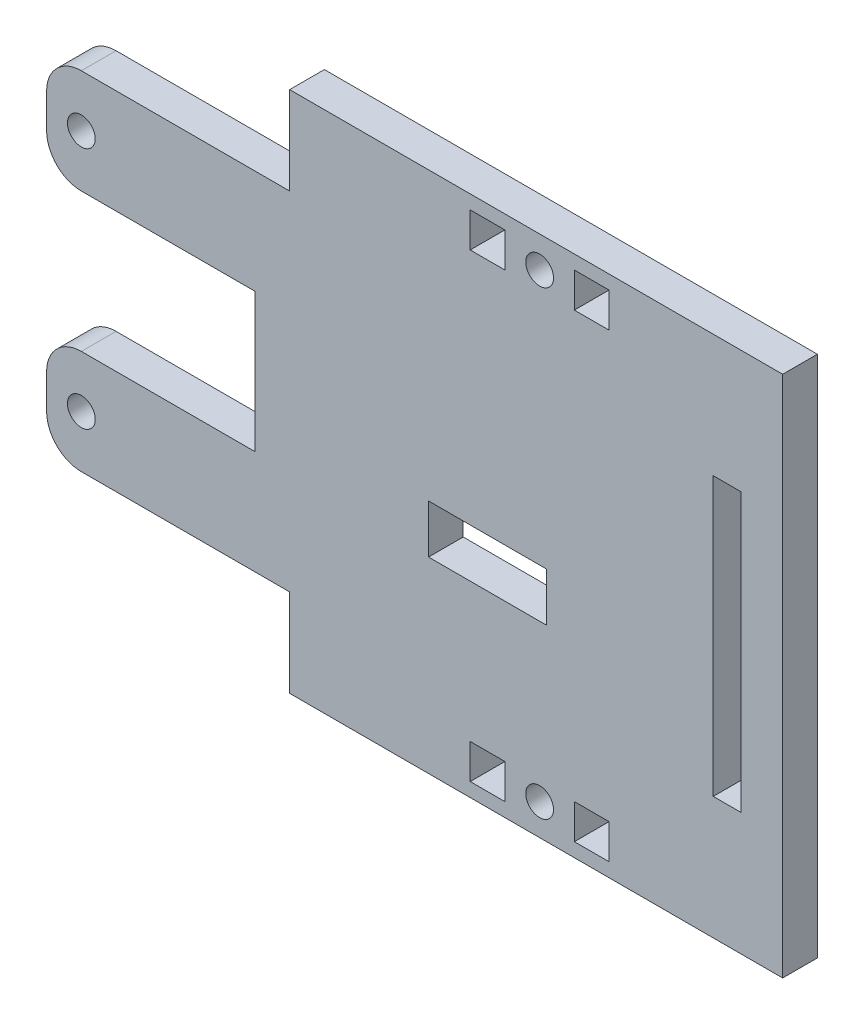
SolidWorks part; units mm, degrees
ref_plane "Plan de face" through (0, 0, 0) normal (0, 0, 1) x (1, 0, 0)
ref_plane "Plan de dessus" through (0, 0, 0) normal (0, 1, 0) x (1, 0, 0)
ref_plane "Plan de droite" through (0, 0, 0) normal (1, 0, 0) x (0, 0, -1)
sketch "Esquisse1" plane through (0, 0, 0) normal (0, 0, 1) x (1, 0, 0)
  line L0 (0, 0) -> (71, 0) construction
  line L1 (0, 37.65) -> (71, 37.65)
  line L2 (71, 37.65) -> (71, -37.65)
  line L3 (0, 37.65) -> (0, -37.65) construction
  line L4 (0, -37.65) -> (71, -37.65)
  line L5 (0, -37.65) -> (0, -25)
  line L6 (0, -25) -> (-35, -25)
  line L7 (-35, -25) -> (-35, -10)
  line L8 (-35, -10) -> (-5, -10)
  line L9 (-5, -10) -> (-5, 10)
  line L10 (-5, 10) -> (-35, 10)
  line L11 (-35, 10) -> (-35, 25)
  line L12 (-35, 25) -> (0, 25)
  line L13 (0, 25) -> (0, 37.65)
  line L14 (-35, 17.5) -> (0, 17.5) construction
  line L16 (37, -3.65) -> (20, -3.65)
  line L17 (37, -3.65) -> (37, -10.65)
  line L18 (37, -10.65) -> (20, -10.65)
  line L19 (20, -3.65) -> (20, -10.65)
  line L20 (37, -3.65) -> (20, -10.65) construction
  line L21 (37, -10.65) -> (20, -3.65) construction
  line L22 (65, 20) -> (61, 20)
  line L23 (65, 20) -> (65, -20)
  line L24 (65, -20) -> (61, -20)
  line L25 (61, 20) -> (61, -20)
  line L26 (65, 20) -> (61, -20) construction
  line L27 (65, -20) -> (61, 20) construction
  circle A0 centre (-30, 17.5) radius 2
  circle A1 centre (-30, -17.5) radius 2
  point P25 (28.5, -7.15)
  point P30 (63, 0)
  point P31 (0, 0)
  line B0 (31, 33.15) -> (41, 33.15) construction
  line B1 (31, 35.65) -> (26, 35.65)
  line B2 (31, 35.65) -> (31, 30.65)
  line B3 (31, 30.65) -> (26, 30.65)
  line B4 (26, 35.65) -> (26, 30.65)
  line B5 (41, 35.65) -> (46, 35.65)
  line B6 (41, 35.65) -> (41, 30.65)
  line B7 (41, 30.65) -> (46, 30.65)
  line B8 (46, 35.65) -> (46, 30.65)
  line B9 (36, 33.15) -> (36, 40.1224) construction
  circle B10 centre (36, 33.15) radius 2
  line B11 (31, -35.65) -> (26, -35.65)
  line B12 (31, -35.65) -> (31, -30.65)
  line B13 (31, -30.65) -> (26, -30.65)
  line B14 (26, -35.65) -> (26, -30.65)
  line B15 (41, -35.65) -> (46, -35.65)
  line B16 (41, -35.65) -> (41, -30.65)
  line B17 (41, -30.65) -> (46, -30.65)
  line B18 (46, -35.65) -> (46, -30.65)
  line B19 (36, -33.15) -> (36, -40.1224) construction
  circle B20 centre (36, -33.15) radius 2
  dimension "D8" = 4
  dimension "D12" = 34
  dimension "D1" = 36
  dimension "D2" = 20
  dimension "D3" = 2
  dimension "D4" = 71
  dimension "D5" = 33.15
  dimension "D6" = 20
  dimension "D7" = 15
  dimension "D9" = 25
  dimension "D10" = 30
  dimension "D11" = 5
  dimension "D13" = 51
  dimension "D14" = 20
  dimension "D15" = 27
  dimension "D16" = 4
  dimension "D17" = 6
  dimension "D18" = 40
  dimension "D19" = 40
sketch_block_instance "Trou M4 plots 5mm-1"
sketch_block "Trou M4 plots 5mm" parameters "D2"=4, "D1"=5, "D3"=5, "D4"=10
sketch_block_instance "Trou M4 plots 5mm-5"
extrude "Boss.-Extru.1" add sketch "Esquisse1" along normal blind 5
fillet "Congé1" radius 5 4 edges at (-35, -25, 2.5) (-35, -10, 2.5) (-35, 10, 2.5) (-35, 25, 2.5)
